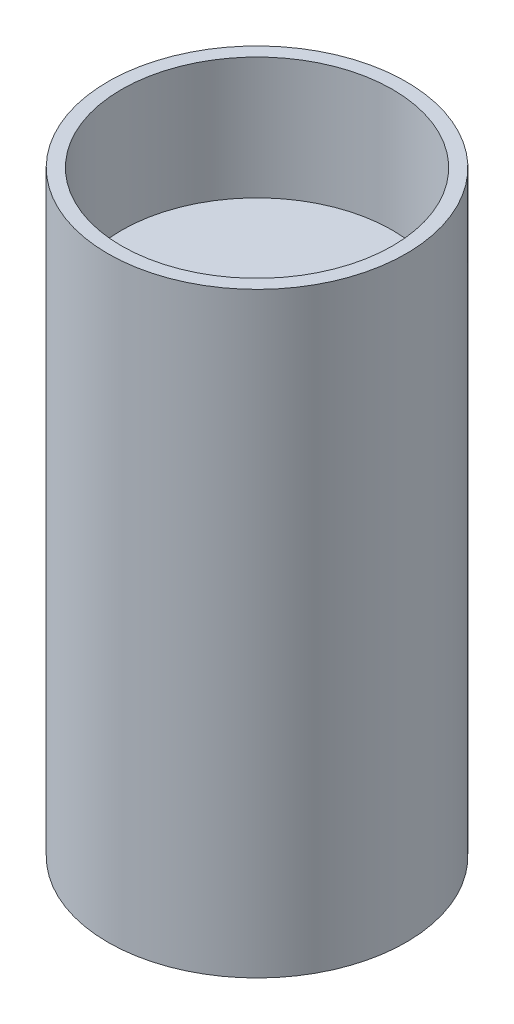
SolidWorks part; units mm, degrees
ref_plane "Alzado" through (0, 0, 0) normal (0, 0, 1) x (1, 0, 0)
ref_plane "Planta" through (0, 0, 0) normal (0, 1, 0) x (1, 0, 0)
ref_plane "Vista lateral" through (0, 0, 0) normal (1, 0, 0) x (0, 0, -1)
sketch "Croquis1" plane through (0, 0, 0) normal (0, 1, 0) x (1, 0, 0)
  circle A0 centre (0, 0) radius 55
  dimension "D1" = 110
extrude "Saliente-Extruir1" add sketch "Croquis1" along normal blind 220
sketch "Croquis2" plane through (0, 0, 0) normal (0, -1, 0) x (1, 0, 0)
  circle A0 centre (0, 0) radius 46.9866
extrude "Cortar-Extruir1" cut sketch "Croquis2" against normal blind 150
sketch "Croquis3" plane through (0, 220, 0) normal (0, 1, 0) x (1, 0, 0)
  circle A0 centre (0, 0) radius 50
  dimension "D1" = 100
extrude "Cortar-Extruir2" cut sketch "Croquis3" against normal blind 45
